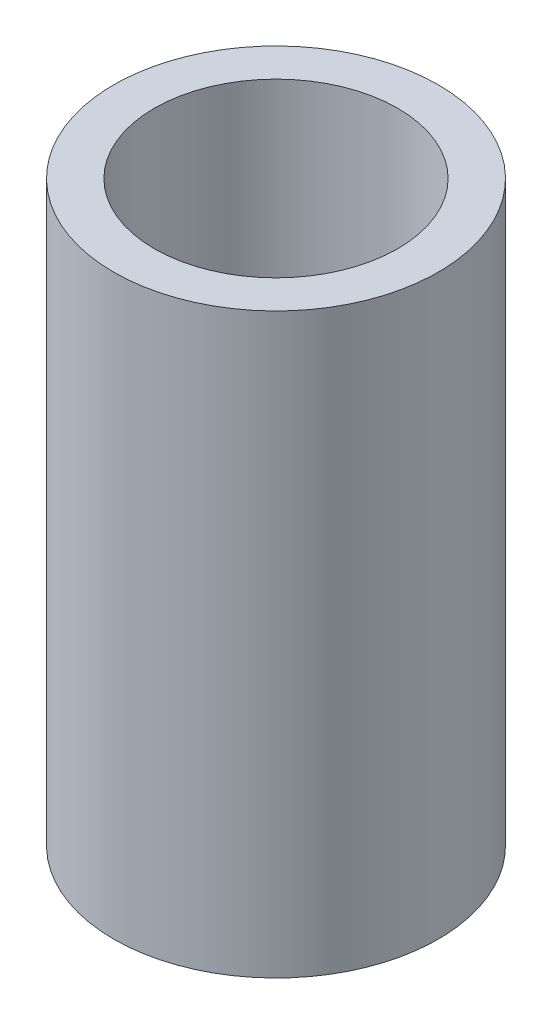
SolidWorks part; units mm, degrees
ref_plane "Front Plane" through (0, 0, 0) normal (0, 0, 1) x (1, 0, 0)
ref_plane "Top Plane" through (0, 0, 0) normal (0, 1, 0) x (1, 0, 0)
ref_plane "Right Plane" through (0, 0, 0) normal (1, 0, 0) x (0, 0, -1)
sketch "Sketch1" plane through (0, 0, 0) normal (0, 1, 0) x (1, 0, 0)
  circle A0 centre (0, 0) radius 6
  circle A1 centre (0, 0) radius 8
  dimension "D1" = 12
  dimension "D2" = 16
extrude "Boss-Extrude1" add sketch "Sketch1" along normal blind 28.477
